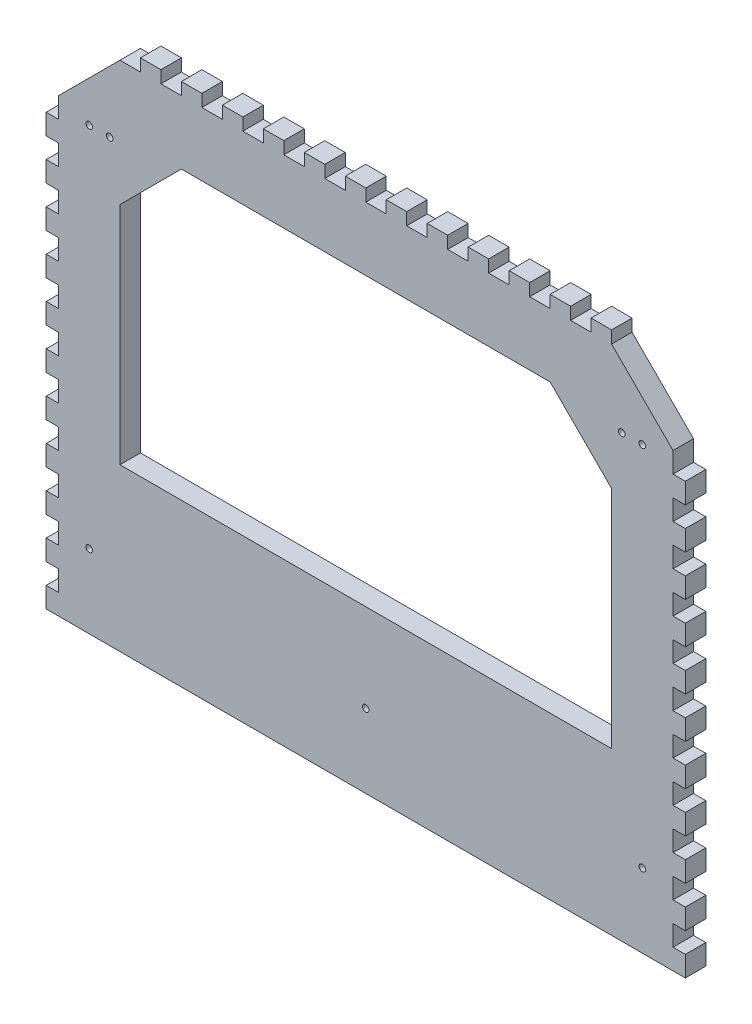
SolidWorks part; units mm, degrees
material "Buche"
ref_plane "Ebene vorne" through (0, 0, 0) normal (0, 0, 1) x (1, 0, 0)
ref_plane "Ebene oben" through (0, 0, 0) normal (0, 1, 0) x (1, 0, 0)
ref_plane "Ebene rechts" through (0, 0, 0) normal (1, 0, 0) x (0, 0, -1)
sketch "Skizze1" plane through (0, 0, 0) normal (0, 0, 1) x (1, 0, 0)
  line L0 (5, 9.9992) -> (5, 19.9757)
  line L1 (4.9569, 0) -> (305, 0)
  line L2 (305, 10) -> (305, 20)
  line L3 (55, 250) -> (65, 250)
  line L4 (5, 220) -> (35, 250)
  line L5 (305, 220) -> (275, 250)
  line L6 (275, 188.9712) -> (245, 218.9712)
  line L7 (35, 78.9712) -> (275, 78.9712)
  line L8 (35, 78.9712) -> (35, 188.9712)
  line L9 (65, 218.9712) -> (245, 218.9712)
  line L10 (275, 78.9712) -> (275, 188.9712)
  line L11 (35, 188.9712) -> (65, 218.9712)
  line L12 (35, 250) -> (45, 250)
  line L13 (305, 0) -> (311, 0)
  line L14 (311, 0) -> (311, 10)
  line L15 (311, 10) -> (305, 10)
  line L16 (305, 30) -> (305, 40)
  line L17 (305, 20) -> (311, 20)
  line L18 (311, 20) -> (311, 30)
  line L19 (311, 30) -> (305, 30)
  line L20 (305, 50) -> (305, 60)
  line L21 (305, 40) -> (311, 40)
  line L22 (311, 40) -> (311, 50)
  line L23 (311, 50) -> (305, 50)
  line L24 (305, 70) -> (305, 80)
  line L25 (305, 60) -> (311, 60)
  line L26 (311, 60) -> (311, 70)
  line L27 (311, 70) -> (305, 70)
  line L28 (305, 90) -> (305, 100)
  line L29 (305, 80) -> (311, 80)
  line L30 (311, 80) -> (311, 90)
  line L31 (311, 90) -> (305, 90)
  line L32 (305, 110) -> (305, 120)
  line L33 (305, 100) -> (311, 100)
  line L34 (311, 100) -> (311, 110)
  line L35 (311, 110) -> (305, 110)
  line L36 (305, 130) -> (305, 140)
  line L37 (305, 120) -> (311, 120)
  line L38 (311, 120) -> (311, 130)
  line L39 (311, 130) -> (305, 130)
  line L40 (305, 150) -> (305, 160)
  line L41 (305, 140) -> (311, 140)
  line L42 (311, 140) -> (311, 150)
  line L43 (311, 150) -> (305, 150)
  line L44 (305, 170) -> (305, 180)
  line L45 (305, 160) -> (311, 160)
  line L46 (311, 160) -> (311, 170)
  line L47 (311, 170) -> (305, 170)
  line L48 (305, 190) -> (305, 200)
  line L49 (305, 180) -> (311, 180)
  line L50 (311, 180) -> (311, 190)
  line L51 (311, 190) -> (305, 190)
  line L52 (305, 210) -> (305, 220)
  line L53 (305, 200) -> (311, 200)
  line L54 (311, 200) -> (311, 210)
  line L55 (311, 210) -> (305, 210)
  line L56 (4.9569, 0) -> (-1, 0)
  line L57 (-1, 0) -> (-1, 9.9992)
  line L58 (-1, 9.9992) -> (5, 9.9992)
  line L59 (5, 29.9992) -> (5, 39.9757)
  line L60 (-1, 20) -> (-1, 29.9992)
  line L61 (-1, 29.9992) -> (5, 29.9992)
  line L62 (-1, 40) -> (5, 39.9757)
  line L63 (5, 49.9992) -> (5, 59.9757)
  line L64 (-1, 40) -> (-1, 49.9992)
  line L65 (5, 70) -> (5, 80)
  line L66 (5, 220) -> (5, 219.9757)
  line L67 (0, 70) -> (5, 70)
  line L68 (5, 90) -> (5, 100)
  line L70 (0, 90) -> (5, 90)
  line L71 (5, 110) -> (5, 120)
  line L73 (0, 110) -> (5, 110)
  line L74 (5, 130) -> (5, 140)
  line L76 (0, 130) -> (5, 130)
  line L77 (5, 150) -> (5, 160)
  line L79 (0, 150) -> (5, 150)
  line L80 (-1, 49.9992) -> (5, 49.9992)
  line L81 (-1, 60) -> (5, 59.9757)
  line L82 (5, 69.9992) -> (5, 79.9757)
  line L83 (-1, 60) -> (-1, 69.9992)
  line L84 (-1, 69.9992) -> (5, 69.9992)
  line L85 (-1, 80) -> (5, 79.9757)
  line L86 (5, 89.9992) -> (5, 99.9757)
  line L87 (-1, 80) -> (-1, 89.9992)
  line L88 (-1, 89.9992) -> (5, 89.9992)
  line L89 (-1, 20) -> (5, 19.9757)
  line L90 (-1, 100) -> (5, 99.9757)
  line L91 (0, 60) -> (5, 60)
  line L92 (0, 80) -> (5, 80)
  line L93 (0, 100) -> (5, 100)
  line L94 (0, 120) -> (5, 120)
  line L95 (0, 140) -> (5, 140)
  line L96 (5, 109.9992) -> (5, 119.9757)
  line L97 (-1, 100) -> (-1, 109.9992)
  line L98 (-1, 109.9992) -> (5, 109.9992)
  line L99 (45, 250) -> (45, 256)
  line L100 (45, 256) -> (55, 256)
  line L101 (55, 256) -> (55, 250)
  line L102 (65, 250) -> (65, 256)
  line L103 (65, 256) -> (75, 256)
  line L104 (75, 256) -> (75, 250)
  line L105 (75, 250) -> (85, 250)
  line L106 (85, 250) -> (85, 256)
  line L107 (85, 256) -> (95, 256)
  line L108 (95, 256) -> (95, 250)
  line L109 (95, 250) -> (105, 250)
  line L110 (105, 250) -> (105, 256)
  line L111 (105, 256) -> (115, 256)
  line L112 (115, 256) -> (115, 250)
  line L113 (115, 250) -> (125, 250)
  line L114 (125, 250) -> (125, 256)
  line L115 (125, 256) -> (135, 256)
  line L116 (135, 256) -> (135, 250)
  line L117 (135, 250) -> (145, 250)
  line L118 (145, 250) -> (145, 256)
  line L119 (145, 256) -> (155, 256)
  line L120 (155, 256) -> (155, 250)
  line L121 (155, 250) -> (165, 250)
  line L122 (165, 250) -> (165, 256)
  line L123 (165, 256) -> (175, 256)
  line L124 (175, 256) -> (175, 250)
  line L125 (175, 250) -> (185, 250)
  line L126 (185, 250) -> (185, 256)
  line L127 (185, 256) -> (195, 256)
  line L128 (195, 256) -> (195, 250)
  line L129 (195, 250) -> (205, 250)
  line L130 (205, 250) -> (205, 256)
  line L131 (205, 256) -> (215, 256)
  line L132 (215, 256) -> (215, 250)
  line L133 (215, 250) -> (225, 250)
  line L134 (225, 250) -> (225, 256)
  line L135 (225, 256) -> (235, 256)
  line L136 (235, 256) -> (235, 250)
  line L137 (235, 250) -> (245, 250)
  line L138 (245, 250) -> (245, 256)
  line L139 (245, 256) -> (255, 256)
  line L140 (255, 256) -> (255, 250)
  line L141 (255, 250) -> (265, 250)
  line L142 (265, 250) -> (265, 256)
  line L143 (265, 256) -> (275, 256)
  line L144 (275, 256) -> (275, 250)
  line L145 (-1, 120) -> (5, 119.9757)
  line L146 (5, 129.9992) -> (5, 139.9757)
  line L147 (-1, 120) -> (-1, 129.9992)
  line L148 (-1, 129.9992) -> (5, 129.9992)
  line L149 (-1, 140) -> (5, 139.9757)
  line L150 (5, 149.9992) -> (5, 159.9757)
  line L151 (-1, 140) -> (-1, 149.9992)
  line L152 (-1, 149.9992) -> (5, 149.9992)
  line L153 (-1, 160) -> (5, 159.9757)
  line L154 (5, 169.9992) -> (5, 179.9757)
  line L155 (-1, 160) -> (-1, 169.9992)
  line L156 (-1, 169.9992) -> (5, 169.9992)
  line L157 (-1, 180) -> (5, 179.9757)
  line L158 (5, 189.9992) -> (5, 199.9757)
  line L159 (-1, 180) -> (-1, 189.9992)
  line L160 (-1, 189.9992) -> (5, 189.9992)
  line L161 (-1, 200) -> (5, 199.9757)
  line L162 (5, 209.9992) -> (5, 219.9757)
  line L163 (-1, 200) -> (-1, 209.9992)
  line L164 (-1, 209.9992) -> (5, 209.9992)
  line L166 (-1, 220) -> (5, 219.9757) [skipped]
  circle A0 centre (290, 215) radius 1.6
  circle A1 centre (280, 215) radius 1.6
  circle A2 centre (20, 215) radius 1.6
  circle A3 centre (30, 215) radius 1.6
  circle A4 centre (20, 36) radius 1.6
  circle A5 centre (155, 36) radius 1.6
  circle A6 centre (290, 36) radius 1.6
  dimension "D2" = 11
  dimension "D1" = 12
  dimension "D3" = 300
  dimension "D4" = 312
  dimension "D5" = 6
  dimension "D6" = 6
  dimension "D7" = 6
  dimension "D9" = 11
extrude "Aufsatz-Linear austragen1" add sketch "Skizze1" along normal blind 10
